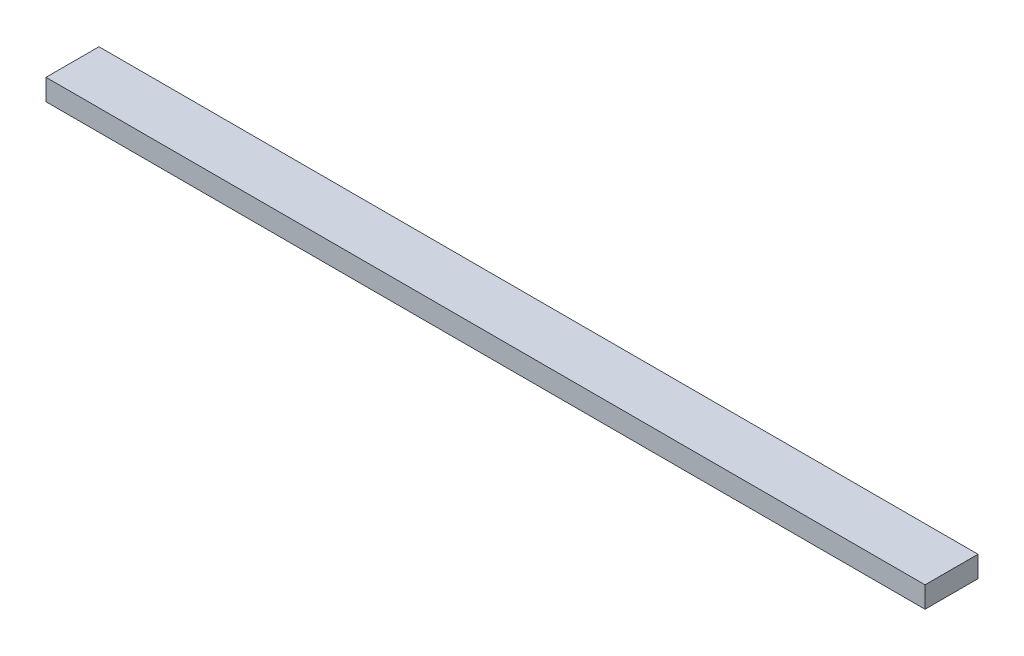
SolidWorks part; units mm, degrees
material "Сосна"
ref_plane "Спереди" through (0, 0, 0) normal (0, 0, 1) x (1, 0, 0)
ref_plane "Сверху" through (0, 0, 0) normal (0, 1, 0) x (1, 0, 0)
ref_plane "Справа" through (0, 0, 0) normal (1, 0, 0) x (0, 0, -1)
sketch "Эскиз1" plane through (0, 0, 0) normal (0, 1, 0) x (1, 0, 0)
  line L1 (0, 25) -> (415, 25)
  line L2 (0, 25) -> (0, 0)
  line L3 (0, 0) -> (415, 0)
  line L4 (415, 25) -> (415, 0)
  dimension "D1" = 25
  dimension "D2" = 415
extrude "Бобышка-Вытянуть1" add sketch "Эскиз1" along normal blind 10
